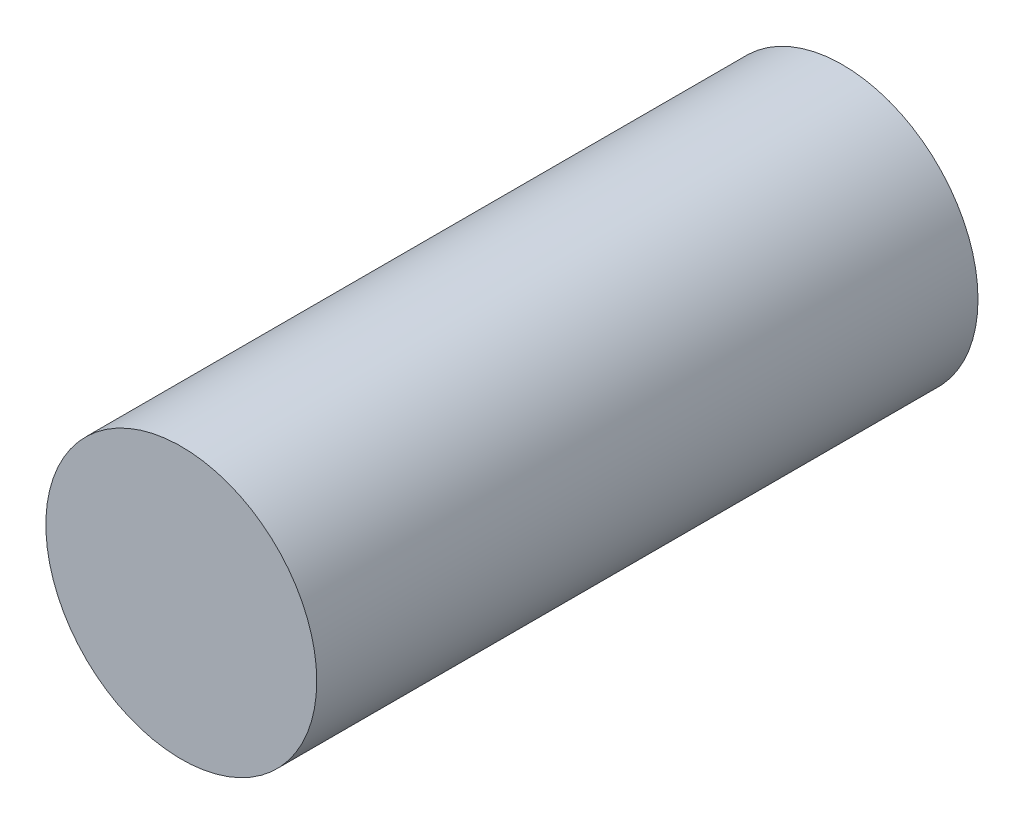
SolidWorks part; units mm, degrees
ref_plane "Front Plane" through (0, 0, 0) normal (0, 0, 1) x (1, 0, 0)
ref_plane "Top Plane" through (0, 0, 0) normal (0, 1, 0) x (1, 0, 0)
ref_plane "Right Plane" through (0, 0, 0) normal (1, 0, 0) x (0, 0, -1)
sketch "Planform" plane through (0, 0, 0) normal (0, 1, 0) x (1, 0, 0)
  line L0 (0, 0) -> (0, -7497.1177)
  line L1 (-17711.9405, -11444.2752) -> (-17711.9405, -14068.2664)
  line L2 (0, -1874.2794) -> (-17711.9405, -12100.273) construction
  line L3 (0, -1874.2794) -> (-6644.0672, -1874.2794) construction
  line L4 (0, 0) -> (-17711.9405, -11444.2752)
  line L5 (0, -7497.1177) -> (-17711.9405, -14068.2664)
  dimension "D1" = 7497.1177
  dimension "D2" = 2623.9912
  dimension "D3" = 1874.2794
  dimension "D4" = 655.9978
  dimension "D5" = 30
  dimension "D6" = 17711.9405
sketch "Sketch1" plane through (0, 0, 0) normal (0, 0, 1) x (1, 0, 0)
  circle A0 centre (0, 0) radius 1209.8064
  dimension "D1" = 2419.6129
extrude "Boss-Extrude1" add sketch "Sketch1" along normal blind 5906.115
equation "\"Root Chord\"= 2 * \"S_ref\" / ( \"Span\" * ( 1 + \"Taper Ratio\" ) )"
equation "\"Tip Chord\"= \"Root Chord\" * \"Taper Ratio\""
equation "\"D2@Planform\" = \"Tip Chord\""
equation "\"D3@Planform\" = \"Root Chord\" * 0.25"
equation "\"D4@Planform\" = \"Tip Chord\" * 0.25"
equation "\"Swept Angle\"= 30'Input"
equation "\"D5@Planform\" = \"Swept Angle\""
equation "\"Span\"= 116.22008186256'Input"
equation "\"D6@Planform\" = \"Span\" / 2"
equation "\"AR\"= 8'Input"
equation "\"S_ref\"= 1929.58677544867'Input"
equation "\"Taper Ratio\"= 0.35'Input"
equation "\"D1@Planform\"=\"Root Chord\""
